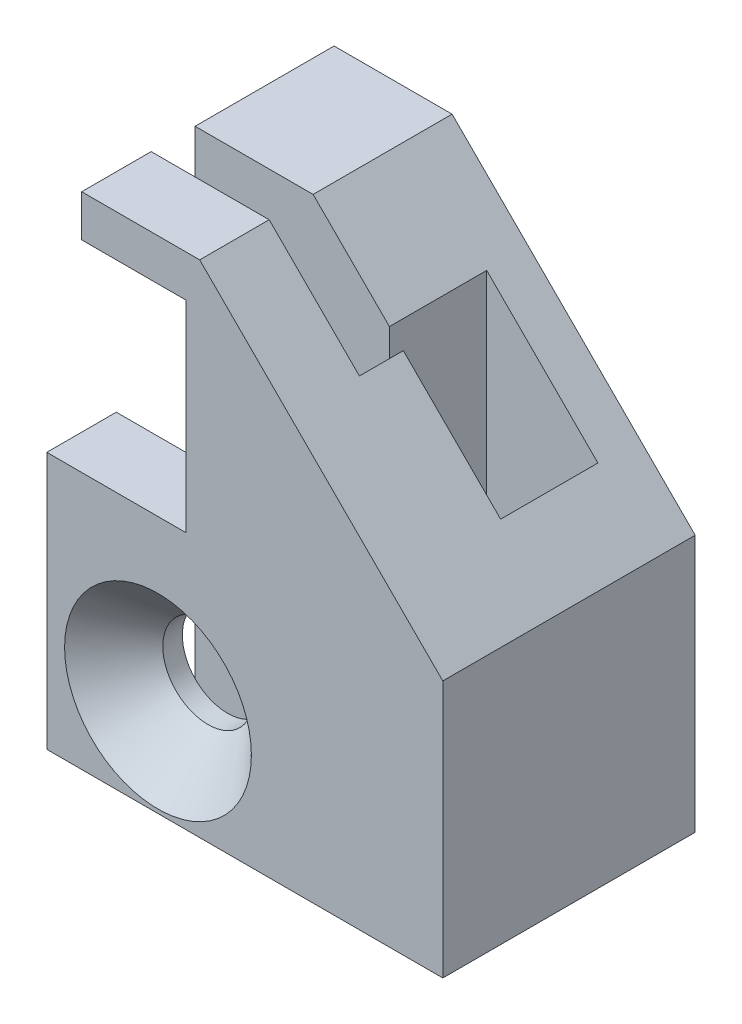
SolidWorks part; units mm, degrees
ref_plane "Alzado" through (0, 0, 0) normal (0, 0, 1) x (1, 0, 0)
ref_plane "Planta" through (0, 0, 0) normal (0, 1, 0) x (1, 0, 0)
ref_plane "Vista lateral" through (0, 0, 0) normal (1, 0, 0) x (0, 0, -1)
sketch "Croquis1" plane through (0, 0, 0) normal (0, 0, 1) x (1, 0, 0)
  line L0 (-126.2451, -73.9999) -> (-113.2545, -73.9999)
  line L1 (-113.2545, -73.9999) -> (-113.2545, -64.7452)
  line L2 (-113.2545, -64.7452) -> (-121.9998, -55.9999)
  line L3 (-121.9998, -55.9999) -> (-126.2451, -55.9999)
  line L4 (-126.2451, -55.9999) -> (-126.2451, -57.4999)
  line L6 (-126.2451, -57.4999) -> (-122.4951, -57.4999)
  line L7 (-122.4951, -57.4999) -> (-122.4951, -64.7452)
  line L8 (-126.2451, -64.7452) -> (-122.4951, -64.7452)
  line L9 (-126.2451, -64.7452) -> (-126.2451, -73.9999)
  circle A0 centre (-123.4998, -70.4999) radius 1.625
  dimension "D1" = 3.25
  dimension "D2" = 122.4951
  dimension "D3" = 113.2545
  dimension "D4" = 123.4998
  dimension "D5" = 126.2451
  dimension "D6" = 57.4999
  dimension "D7" = 64.7452
  dimension "D8" = 70.4999
  dimension "D9" = 73.9999
extrude "Saliente-Extruir1" add sketch "Croquis1" along normal blind 2.5
sketch "Croquis2" plane through (0, 0, 0) normal (0, 0, -1) x (-1, 0, 0)
  line L0 (119.9998, -57.9999) -> (119.9998, -71.9999)
  line L1 (113.2545, -64.7452) -> (121.9998, -55.9999) construction
  line L2 (119.9998, -71.9999) -> (119.9998, -57.9999) construction
  line L3 (119.9998, -71.9999) -> (121.9998, -73.9999)
  line L4 (126.2451, -73.9999) -> (113.2545, -73.9999) construction
  line L5 (121.9998, -73.9999) -> (113.2545, -73.9999)
  line L6 (113.2545, -73.9999) -> (113.2545, -64.7452)
  line L7 (113.2545, -64.7452) -> (119.9998, -57.9999)
extrude "Saliente-Extruir2" add sketch "Croquis2" along normal up to vertex (1.58 mm away)
sketch "Croquis3" plane through (0, 0, -1.58) normal (0, 0, -1) x (-1, 0, 0)
  line L0 (113.2545, -73.9999) -> (113.2545, -64.7452)
  line L1 (113.2545, -64.7452) -> (115.2545, -62.7452)
  line L2 (119.9998, -57.9999) -> (113.2545, -64.7452) construction
  line L4 (115.2545, -62.7452) -> (115.2545, -73.9999)
  line L5 (113.2545, -73.9999) -> (121.9998, -73.9999) construction
  line L7 (115.2545, -73.9999) -> (113.2545, -73.9999)
  line L11 (119.2545, -73.9999) -> (121.9998, -73.9999)
  line L14 (121.9998, -73.9999) -> (126.2451, -73.9999)
  line L15 (126.2451, -73.9999) -> (126.2451, -64.7452)
  line L16 (126.2451, -64.7452) -> (126.2451, -55.9999)
  line L17 (126.2451, -55.9999) -> (121.9998, -55.9999)
  line L18 (121.9998, -55.9999) -> (119.9998, -57.9999)
  line L19 (113.2545, -64.7452) -> (113.2545, -73.9999) construction
  line L20 (119.2545, -73.9999) -> (119.2545, -58.7452)
  line L21 (119.2545, -58.7452) -> (119.9998, -57.9999)
  circle A0 centre (123.4998, -70.4999) radius 1.625
  dimension "D1" = 3.25
  dimension "D3" = 6
  dimension "D4" = 10.2453
  dimension "D5" = 3.5
extrude "Saliente-Extruir3" add sketch "Croquis3" along normal up to vertex (3.5 mm away)
sketch "Croquis5" plane through (0, 0, -5.08) normal (0, 0, -1) x (-1, 0, 0)
  line L0 (113.2545, -73.9999) -> (126.2451, -73.9999)
  line L1 (126.2451, -73.9999) -> (126.2451, -55.9999)
  line L2 (126.2451, -55.9999) -> (121.9998, -55.9999)
  line L3 (121.9998, -55.9999) -> (113.2545, -64.7452)
  line L4 (113.2545, -64.7452) -> (113.2545, -73.9999)
  line L5 (119.2545, -73.9999) -> (126.2451, -73.9999) construction
  circle A0 centre (123.4998, -70.4999) radius 1.625
  dimension "D1" = 3.25
  dimension "D2" = 9.2547
extrude "Saliente-Extruir4" add sketch "Croquis5" along normal blind 1.5
sketch "Croquis6" plane through (0, -73.9999, 0) normal (0, -1, 0) x (1, 0, 0)
  line L0 (-115.2545, -5.08) -> (-115.2545, -1.58) construction
  line L1 (-121.9998, -1.58) -> (-118.7545, -1.58)
  line L2 (-121.9998, -1.58) -> (-121.9998, 0)
  line L3 (-121.9998, 0) -> (-118.7545, 0)
  line L4 (-118.7545, -1.58) -> (-118.7545, 0)
  line L5 (-126.2451, 0) -> (-121.9998, 0) construction
  dimension "D1" = 3.5
extrude "Cortar-Extruir1" cut sketch "Croquis6" against normal up to vertex
sketch "Croquis7" plane through (0, 0, 2.5) normal (0, 0, 1) x (1, 0, 0)
  line L0 (-113.2545, -73.9999) -> (-113.2545, -64.7452) construction
  line L1 (-126.2451, -73.9999) -> (-127.4998, -73.9999)
  line L2 (-127.4998, -73.9999) -> (-127.4998, -64.7452)
  line L3 (-127.4998, -64.7452) -> (-126.2451, -64.7452)
  line L4 (-126.2451, -64.7452) -> (-126.2451, -73.9999)
  line L5 (-126.2451, -73.9999) -> (-113.2545, -73.9999) construction
  dimension "D1" = 14.2453
extrude "Saliente-Extruir5" add sketch "Croquis7" against normal up to vertex
sketch "Croquis8" plane through (0, 0, 2.5) normal (0, 0, 1) x (1, 0, 0)
  circle A1 centre (-123.4998, -70.4999) radius 3.36
  dimension "D1" = 6.7199
extrude "Cortar-Extruir2" cut sketch "Croquis8" against normal blind 1.8 draft 44
sketch "Croquis9" plane through (0, 0, -6.58) normal (0, 0, -1) x (-1, 0, 0)
  line L8 (120.7545, -72.0849) -> (123.4998, -73.6699)
  line L9 (123.4998, -73.6699) -> (124.0714, -73.9999)
  line L10 (113.2545, -73.9999) -> (126.2451, -73.9999) construction
  line L11 (124.0714, -73.9999) -> (126.2451, -73.9999)
  line L12 (126.2451, -73.9999) -> (126.2451, -72.0849)
  line L14 (123.4998, -67.3299) -> (126.2451, -68.9149)
  line L15 (126.2451, -72.0849) -> (126.2451, -68.9149)
  line L16 (113.2545, -64.7452) -> (113.2545, -73.9999) construction
  line L17 (120.7545, -72.0849) -> (120.7545, -68.9149)
  line L18 (120.7545, -68.9149) -> (123.4998, -67.3299)
  dimension "D1" = 7.5
  dimension "D2" = 0.33
  dimension "D3" = 1.915
extrude "Cortar-Extruir3" cut sketch "Croquis9" against normal blind 2.5
